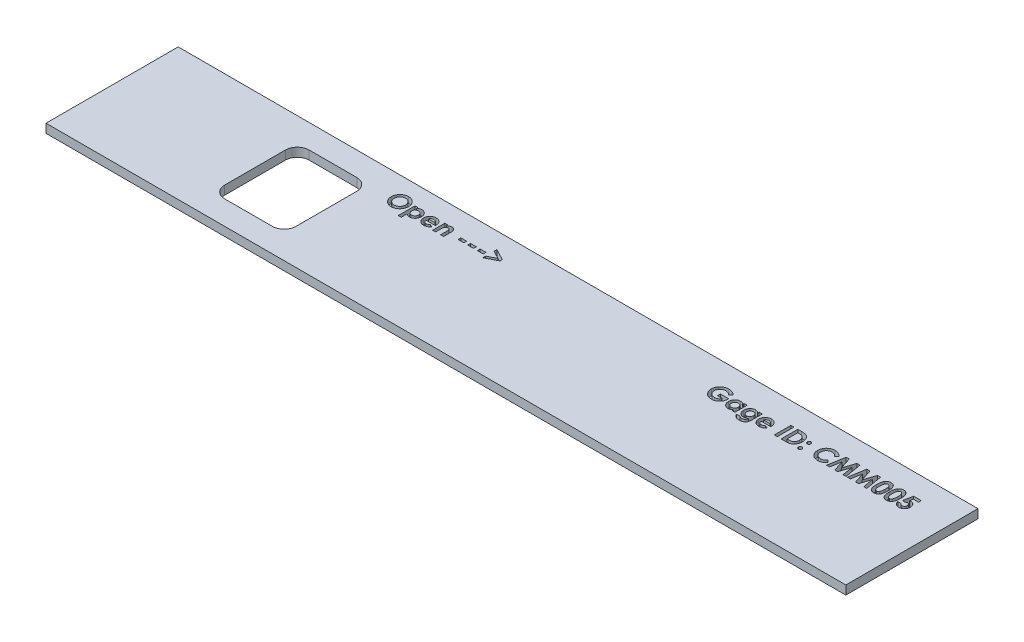
SolidWorks part; units mm, degrees
ref_plane "Front Plane" through (0, 0, 0) normal (0, 0, 1) x (1, 0, 0)
ref_plane "Top Plane" through (0, 0, 0) normal (0, 1, 0) x (1, 0, 0)
ref_plane "Right Plane" through (0, 0, 0) normal (1, 0, 0) x (0, 0, -1)
sketch "Sketch1" plane through (0, 0, 0) normal (0, 1, 0) x (1, 0, 0)
  line L1 (0, 0) -> (167.9, 0)
  line L2 (0, 0) -> (0, 27.75)
  line L3 (0, 27.75) -> (167.9, 27.75)
  line L4 (167.9, 0) -> (167.9, 27.75)
  dimension "D1" = 167.9
  dimension "D2" = 27.75
extrude "Boss-Extrude1" add sketch "Sketch1" along normal blind 1.85
sketch "Sketch2" plane through (0, 1.85, 0) normal (0, 1, 0) x (1, 0, 0)
  line L0 (167.9, 27.75) -> (0, 27.75) construction
  line L1 (30, 22.75) -> (45, 22.75)
  line L2 (30, 22.75) -> (30, 5)
  line L3 (30, 5) -> (45, 5)
  line L4 (45, 22.75) -> (45, 5)
  line L5 (0, 0) -> (167.9, 0) construction
  line L6 (0, 27.75) -> (0, 0) construction
  dimension "D1" = 5
  dimension "D2" = 5
  dimension "D3" = 15
  dimension "D4" = 30
extrude "Cut-Extrude1" cut sketch "Sketch2" against normal through all
fillet "Fillet1" radius 2.5 4 edges at (30, 0.925, -5) (45, 0.925, -5) (30, 0.925, -22.75) (45, 0.925, -22.75)
sketch "Sketch5" plane through (0, 1.85, 0) normal (0, 1, 0) x (1, 0, 0)
  text T0 "<b>Open ---></b>"
extrude "Cut-Extrude3" cut sketch "Sketch5" against normal blind 1.25
sketch "Sketch6" plane through (0, 1.85, 0) normal (0, 1, 0) x (1, 0, 0)
  text T0 "<b>Gage ID: CMM005</b>"
extrude "Cut-Extrude4" cut sketch "Sketch6" against normal blind 1.25
